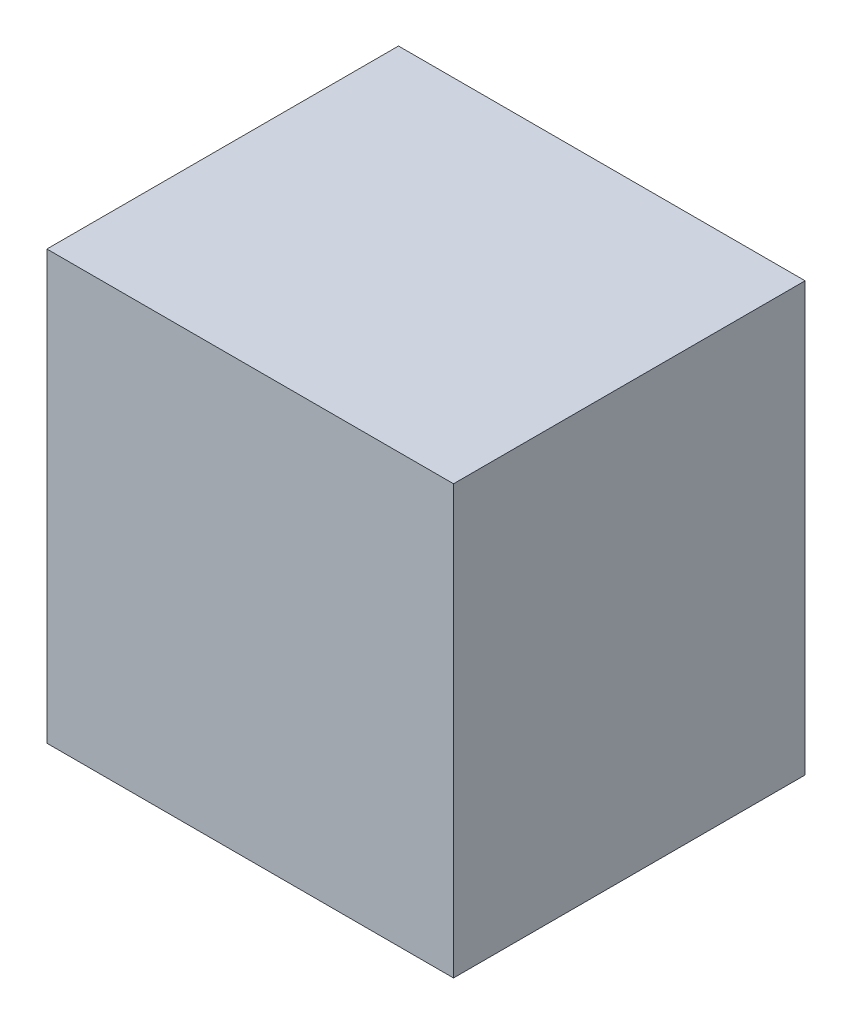
SolidWorks part; units mm, degrees
ref_plane "Front Plane" through (0, 0, 0) normal (0, 0, 1) x (1, 0, 0)
ref_plane "Top Plane" through (0, 0, 0) normal (0, 1, 0) x (1, 0, 0)
ref_plane "Right Plane" through (0, 0, 0) normal (1, 0, 0) x (0, 0, -1)
sketch "Sketch1" plane through (0, 0, 0) normal (0, 1, 0) x (1, 0, 0)
  line L1 (-13.3, -11.5) -> (13.3, -11.5)
  line L2 (-13.3, -11.5) -> (-13.3, 11.5)
  line L3 (-13.3, 11.5) -> (13.3, 11.5)
  line L4 (13.3, -11.5) -> (13.3, 11.5)
  line L5 (-13.3, -11.5) -> (13.3, 11.5) construction
  line L6 (-13.3, 11.5) -> (13.3, -11.5) construction
  point P0 (0, 0)
  dimension "D1" = 26.6
  dimension "D2" = 23
extrude "Boss-Extrude1" add sketch "Sketch1" along normal blind 28
